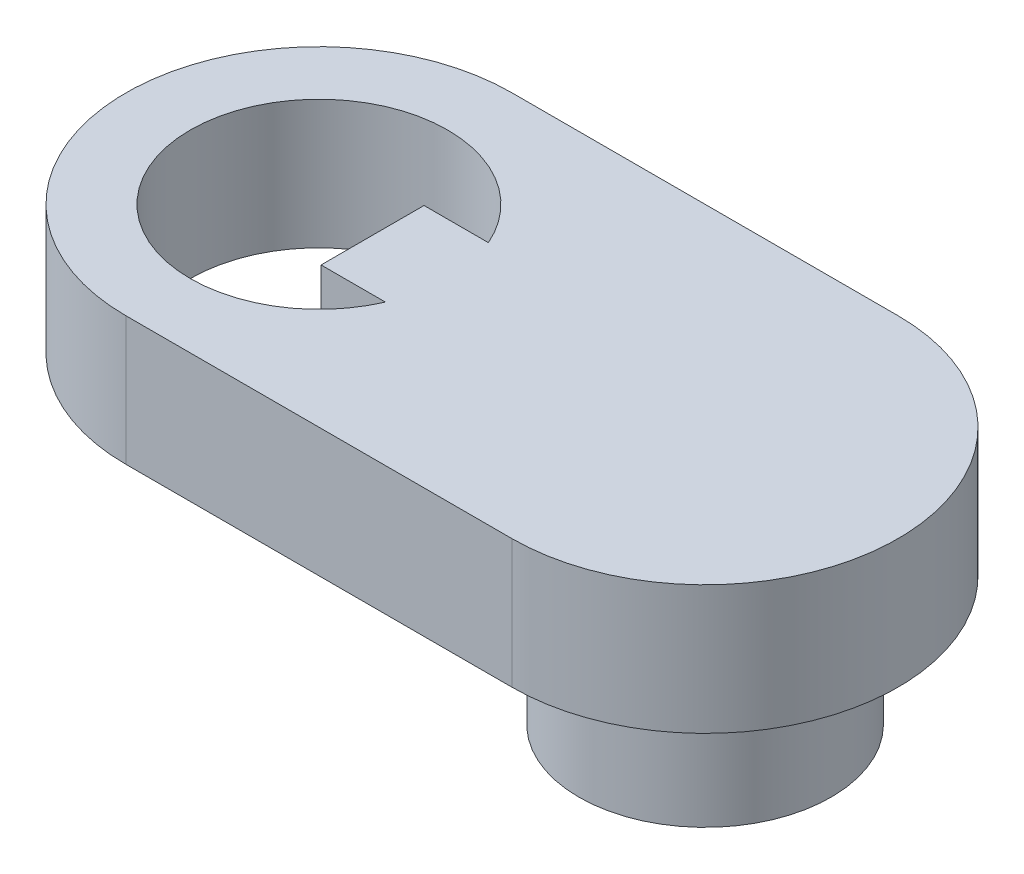
SolidWorks part; units mm, degrees
ref_plane "Front Plane" through (0, 0, 0) normal (0, 0, 1) x (1, 0, 0)
ref_plane "Top Plane" through (0, 0, 0) normal (0, 1, 0) x (1, 0, 0)
ref_plane "Right Plane" through (0, 0, 0) normal (1, 0, 0) x (0, 0, -1)
sketch "Sketch1" plane through (0, 0, 0) normal (0, 1, 0) x (1, 0, 0)
  line L0 (0, 0) -> (15, 0)
  line L1 (0, 0) -> (0, 15) construction
  line L2 (0, 15) -> (15, 15)
  line L3 (15, 0) -> (15, 15) construction
  line L4 (5, 7.5) -> (-5, 7.5) construction
  line L5 (4.5826, 5.5) -> (2.0826, 5.5)
  line L6 (2.0826, 5.5) -> (2.0826, 9.5)
  line L7 (2.0826, 9.5) -> (4.5826, 9.5)
  arc A0 (0, 15) -> (0, 0) centre (0, 7.5) ccw
  arc A1 (15, 0) -> (15, 15) centre (15, 7.5) ccw
  arc A2 (4.5826, 9.5) -> (4.5826, 5.5) centre (0, 7.5) ccw
  circle A3 centre (15, 7.5) radius 5
  dimension "D3" = 10
  dimension "D4" = 10
  dimension "D1" = 15
  dimension "D2" = 15
  dimension "D5" = 2.5
  dimension "D6" = 2
  dimension "D7" = 2
extrude "Boss-Extrude1" add sketch "Sketch1" along normal blind 5
sketch "Sketch2" plane through (0, 5, 0) normal (0, 1, 0) x (1, 0, 0)
  circle A0 centre (15, 7.5) radius 4.9
  circle A1 centre (15, 7.5) radius 5 construction
  dimension "D1" = 0
  dimension "D2" = 9.8
extrude "Boss-Extrude2" add sketch "Sketch2" against normal blind 10
sketch "Sketch4" plane through (0, 5, 0) normal (0, 1, 0) x (-1, 0, 0)
  circle A0 centre (-15, -7.5) radius 5
  circle A1 centre (-15, -7.5) radius 4.9 construction
  dimension "D1" = 0
  dimension "D2" = 10
extrude "Boss-Extrude3" add sketch "Sketch4" against normal blind 1
